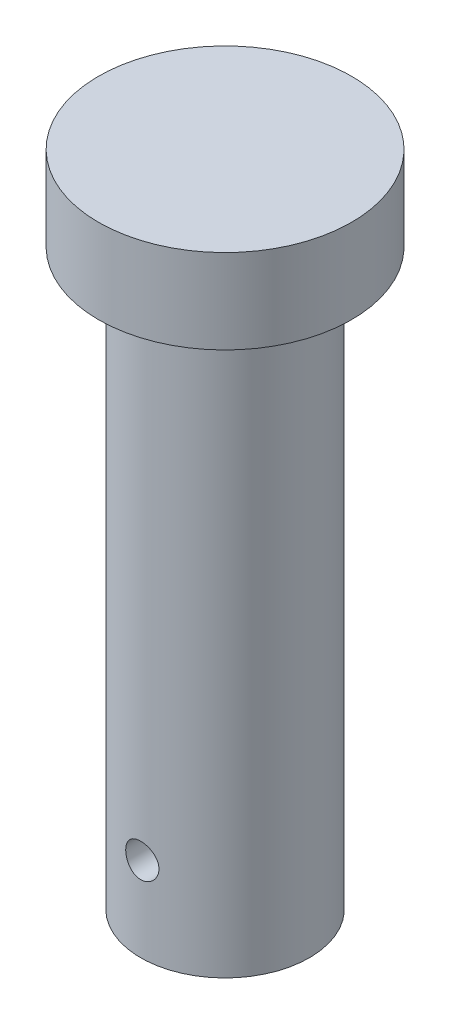
SolidWorks part; units mm, degrees
ref_plane "Front Plane" through (0, 0, 0) normal (0, 0, 1) x (1, 0, 0)
ref_plane "Top Plane" through (0, 0, 0) normal (0, 1, 0) x (1, 0, 0)
ref_plane "Right Plane" through (0, 0, 0) normal (1, 0, 0) x (0, 0, -1)
sketch "Croquis1" plane through (0, 0, 0) normal (0, 1, 0) x (1, 0, 0)
  circle A0 centre (0, 0) radius 22.5
  dimension "D1" = 45
extrude "Saliente-Extruir1" add sketch "Croquis1" against normal blind 15
sketch "Croquis2" plane through (0, -15, 0) normal (0, -1, 0) x (1, 0, 0)
  circle A0 centre (0, 0) radius 15
  dimension "D1" = 30
extrude "Saliente-Extruir2" add sketch "Croquis2" along normal blind 102
sketch "Croquis4" plane through (0, 0, 0) normal (0, 0, 1) x (1, 0, 0)
  line L0 (-15, -117) -> (15, -117) construction
  circle A0 centre (0, -102) radius 2.9577
  dimension "D1" = 15
extrude "Cortar-Extruir1" cut sketch "Croquis4" against normal mid plane 97
